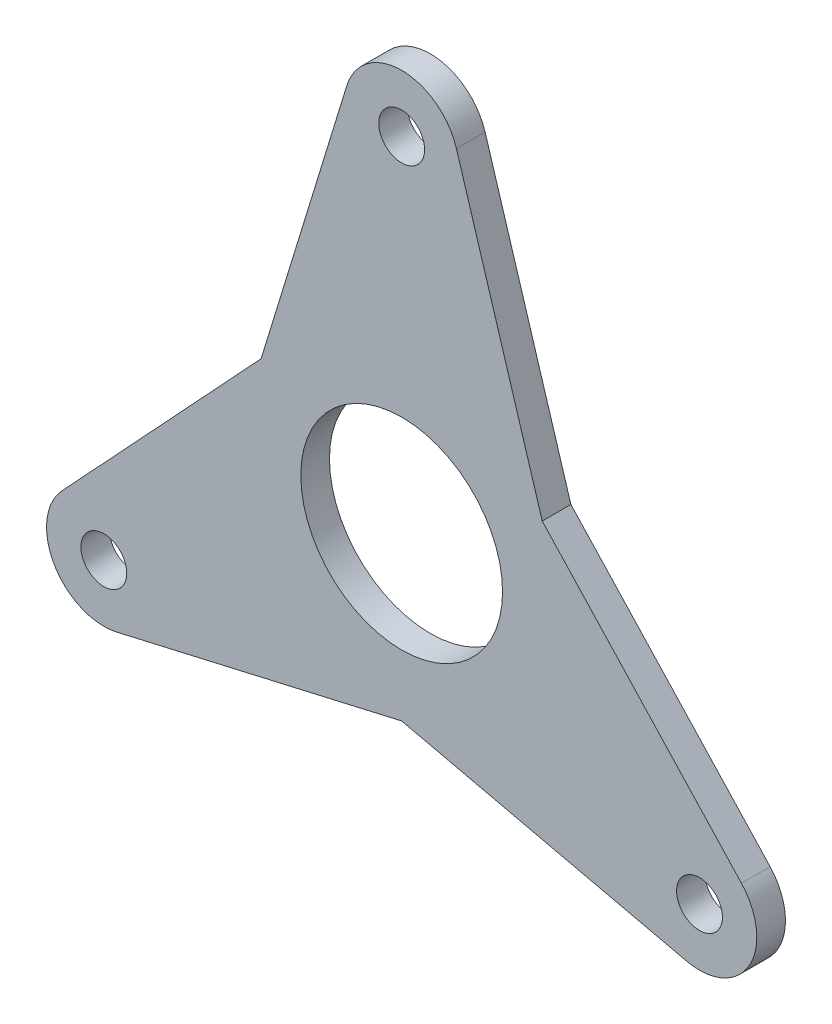
SolidWorks part; units mm, degrees
ref_plane "Front Plane" through (0, 0, 0) normal (0, 0, 1) x (1, 0, 0)
ref_plane "Top Plane" through (0, 0, 0) normal (0, 1, 0) x (1, 0, 0)
ref_plane "Right Plane" through (0, 0, 0) normal (1, 0, 0) x (0, 0, -1)
sketch "Sketch3" plane through (0, 0, 0) normal (0, 0, 1) x (1, 0, 0)
  line L0 (0, 0) -> (0, 38.1) construction
  line L1 (-6.0707, 39.9627) -> (-15.5736, 8.9914)
  line L2 (6.0707, 39.9627) -> (15.5736, 8.9914)
  line L3 (37.644, -14.724) -> (15.5736, 8.9914)
  line L4 (31.5734, -25.2387) -> (0, -17.9828)
  line L5 (-31.5734, -25.2387) -> (0, -17.9828)
  line L6 (-37.644, -14.724) -> (-15.5736, 8.9914)
  circle A0 centre (0, 0) radius 17.526 construction
  circle A1 centre (0, 0) radius 11.176
  circle A2 centre (0, 38.1) radius 2.54
  arc A3 (6.0707, 39.9627) -> (-6.0707, 39.9627) centre (0, 38.1) ccw
  arc A4 (31.5734, -25.2387) -> (37.644, -14.724) centre (32.9956, -19.05) ccw
  circle A5 centre (32.9956, -19.05) radius 2.54
  arc A6 (-37.644, -14.724) -> (-31.5734, -25.2387) centre (-32.9956, -19.05) ccw
  circle A7 centre (-32.9956, -19.05) radius 2.54
  point P6 (33.2228, -17.7268)
  point P11 (0, 0)
  point P12 (-16.3835, 8.1212)
  point P25 (0, 0)
  point P26 (-15.6639, 8.697)
  point P27 (0, 0)
  dimension "D1" = 22.352
  dimension "D2" = 35.052
  dimension "D3" = 5.08
  dimension "D4" = 12.7
  dimension "D5" = 38.1
  dimension "D6" = 3
extrude "Boss-Extrude2" add sketch "Sketch3" along normal blind 3.175
